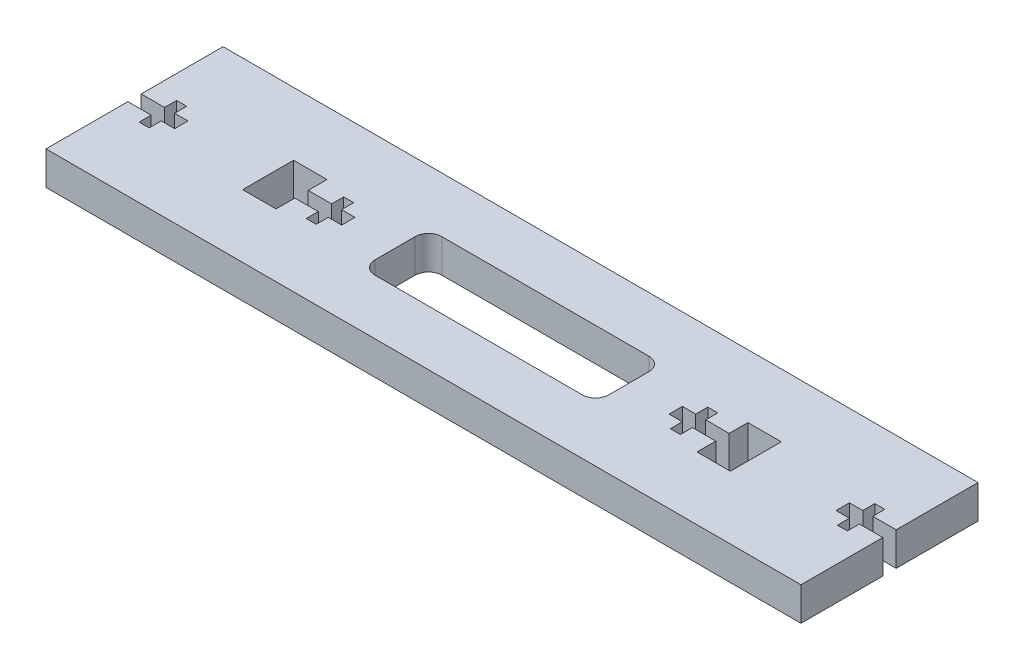
SolidWorks part; units mm, degrees
material "Acrílico (médio-alto impacto)"
ref_plane "Plano frontal" through (0, 0, 0) normal (0, 0, 1) x (1, 0, 0)
ref_plane "Plano superior" through (0, 0, 0) normal (0, 1, 0) x (1, 0, 0)
ref_plane "Plano direito" through (0, 0, 0) normal (1, 0, 0) x (0, 0, -1)
sketch "Esboço1" plane through (0, 0, 0) normal (0, 1, 0) x (1, 0, 0)
  line L1 (-76.7364, -5.6593) -> (36.2636, -5.6593)
  line L2 (-76.7364, -5.6593) -> (-76.7364, -32.1593)
  line L3 (-76.7364, -32.1593) -> (36.2636, -32.1593)
  line L4 (36.2636, -5.6593) -> (36.2636, -32.1593)
extrude "Ressalto-extrusão1" add sketch "Esboço1" along normal blind 5
sketch "Esboço2" plane through (0, 5, 0) normal (0, 1, 0) x (1, 0, 0)
  line L0 (36.2636, -32.1593) -> (36.2636, -5.6593) construction
  line L1 (16.2636, -15.1043) -> (11.2636, -15.1043)
  line L2 (16.2636, -15.1043) -> (16.2636, -22.7243)
  line L3 (16.2636, -22.7243) -> (11.2636, -22.7243)
  line L4 (11.2636, -15.1043) -> (11.2636, -22.7243)
  line L5 (36.2636, -5.6593) -> (-76.7364, -5.6593) construction
  line L9 (-76.7364, -5.6593) -> (-76.7364, -32.1593) construction
  line L10 (-56.7364, -15.1043) -> (-51.7364, -15.1043)
  line L11 (-56.7364, -15.1043) -> (-56.7364, -22.7243)
  line L12 (-56.7364, -22.7243) -> (-51.7364, -22.7243)
  line L13 (-51.7364, -15.1043) -> (-51.7364, -22.7243)
  dimension "D1" = 20
  dimension "D2" = 9.445
  dimension "D3" = 20
extrude "Corte-extrusão1" cut sketch "Esboço2" against normal blind 5
sketch "Esboço3" plane through (0, 5, 0) normal (0, 1, 0) x (1, 0, 0)
  line L0 (-76.7364, -5.6593) -> (-76.7364, -32.1593) construction
  line L1 (-76.7364, -17.9093) -> (-73.2364, -17.9093)
  line L2 (-76.7364, -17.9093) -> (-76.7364, -19.9093)
  line L3 (-76.7364, -19.9093) -> (-73.2364, -19.9093)
  line L4 (-76.7364, -32.1593) -> (36.2636, -32.1593) construction
  line L5 (-73.2364, -19.9093) -> (-73.2364, -21.7093)
  line L6 (-71.7364, -16.1093) -> (-73.2364, -16.1093)
  line L7 (-71.7364, -16.1093) -> (-71.7364, -17.9093)
  line L8 (-71.7364, -21.7093) -> (-73.2364, -21.7093)
  line L9 (-73.2364, -16.1093) -> (-73.2364, -17.9093)
  line L10 (-71.7364, -17.9093) -> (-69.7364, -17.9093)
  line L12 (-71.7364, -19.9093) -> (-69.7364, -19.9093)
  line L13 (-69.7364, -17.9093) -> (-69.7364, -19.9093)
  line L14 (-71.7364, -19.9093) -> (-71.7364, -21.7093)
  line L15 (36.2636, -5.6593) -> (-76.7364, -5.6593) construction
  line L16 (-51.7364, -22.7243) -> (-51.7364, -15.1043) construction
  line L17 (-51.7364, -17.9093) -> (-48.2364, -17.9093)
  line L18 (-51.7364, -17.9093) -> (-51.7364, -19.9093)
  line L19 (-51.7364, -19.9093) -> (-48.2364, -19.9093)
  line L21 (-48.2364, -19.9093) -> (-48.2364, -21.7093)
  line L22 (-46.7364, -16.1093) -> (-48.2364, -16.1093)
  line L23 (-46.7364, -16.1093) -> (-46.7364, -17.9093)
  line L24 (-46.7364, -21.7093) -> (-48.2364, -21.7093)
  line L25 (-48.2364, -16.1093) -> (-48.2364, -17.9093)
  line L26 (-44.7364, -17.9093) -> (-46.7364, -17.9093)
  line L27 (-44.7364, -17.9093) -> (-44.7364, -19.9093)
  line L28 (-44.7364, -19.9093) -> (-46.7364, -19.9093)
  line L30 (-46.7364, -19.9093) -> (-46.7364, -21.7093)
  dimension "D1" = 1.8
  dimension "D2" = 1.8
  dimension "D3" = 1.8
  dimension "D4" = 1.8
  dimension "D5" = 12.25
  dimension "D6" = 12.25
  dimension "D7" = 1.8
  dimension "D8" = 1.8
  dimension "D9" = 1.8
  dimension "D10" = 1.8
  dimension "D11" = 12.25
ref_plane "Plano1" through (-20.2364, 0, 0) normal (-1, 0, 0) x (0, 0, 1)
extrude "Corte-extrusão2" cut sketch "Esboço3" against normal blind 5
mirror "Espelhar1" about plane through (-20.2364, 0, 0) normal (-1, 0, 0) of "Corte-extrusão2"
sketch "Esboço4" plane through (0, 0, 0) normal (0, -1, 0) x (1, 0, 0)
  line L0 (36.2636, 5.6593) -> (-76.7364, 5.6593) construction
  line L1 (-4.7364, 13.9093) -> (-35.7364, 13.9093)
  line L2 (-2.7364, 15.9093) -> (-2.7364, 21.9093)
  line L3 (-4.7364, 23.9093) -> (-35.7364, 23.9093)
  line L4 (-37.7364, 15.9093) -> (-37.7364, 21.9093)
  line L6 (-76.7364, 32.1593) -> (36.2636, 32.1593) construction
  line L7 (36.2636, 32.1593) -> (36.2636, 19.9093) construction
  line L8 (-76.7364, 19.9093) -> (-76.7364, 32.1593) construction
  arc A0 (-37.7364, 15.9093) -> (-35.7364, 13.9093) centre (-35.7364, 15.9093) ccw
  arc A1 (-37.7364, 21.9093) -> (-35.7364, 23.9093) centre (-35.7364, 21.9093) cw
  arc A2 (-4.7364, 23.9093) -> (-2.7364, 21.9093) centre (-4.7364, 21.9093) cw
  arc A3 (-4.7364, 13.9093) -> (-2.7364, 15.9093) centre (-4.7364, 15.9093) ccw
  dimension "D5" = 2
  dimension "D1" = 8.25
  dimension "D2" = 8.25
  dimension "D3" = 39
  dimension "D4" = 39
extrude "Corte-extrusão3" cut sketch "Esboço4" against normal blind 10
